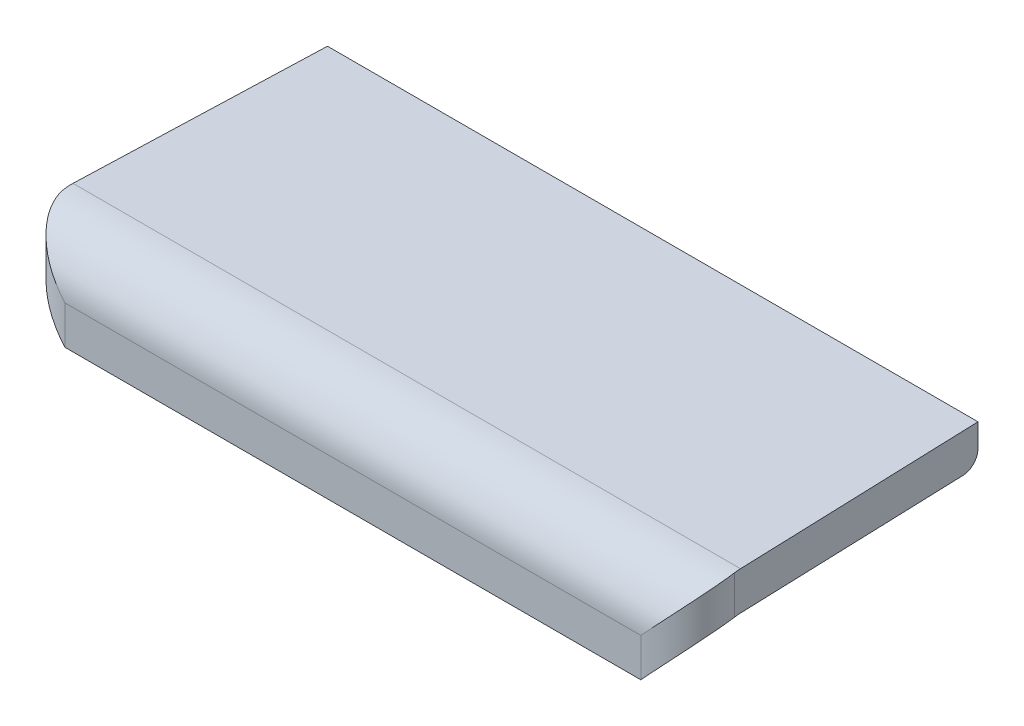
SolidWorks part; units mm, degrees
material "PF"
ref_plane "Спереди" through (0, 0, 0) normal (0, 0, 1) x (1, 0, 0)
ref_plane "Сверху" through (0, 0, 0) normal (0, 1, 0) x (1, 0, 0)
ref_plane "Справа" through (0, 0, 0) normal (1, 0, 0) x (0, 0, -1)
sketch "Эскиз1" plane through (0, 0, 0) normal (1, 0, 0) x (0, 0, -1)
  line L0 (-63.6775, 0) -> (17.5893, 0) construction
  line L1 (0, 14.5278) -> (0, -23.6564) construction
  line L2 (-49.5, 0) -> (0, 0)
  line L4 (-49.5, -2.5) -> (0, -2.5)
  line L5 (0, 0) -> (0, -2.5)
  line L6 (-53, -6) -> (-53, -3.5)
  line L7 (-53, 5.3663) -> (-53, -14.1912) construction
  arc A0 (-53, -6) -> (-49.5, -2.5) centre (-49.5, -6) cw
  arc A1 (-53, -3.5) -> (-49.5, 0) centre (-49.5, -3.5) cw
  point P16 (-53, 0)
  dimension "D3" = 3.5
  dimension "D4" = 3.5
  dimension "D1" = 53
  dimension "D2" = 2.5
extrude "Бобышка-Вытянуть1" add sketch "Эскиз1" along normal mid plane 44
sketch "Эскиз2" plane through (0, 0, 0) normal (0, 1, 0) x (1, 0, 0)
  line L0 (0, 2.7123) -> (0, -68.9812) construction
  line L1 (-30.0519, 0) -> (26.7974, 0) construction
  line L2 (-33.3063, -58) -> (31.5752, -58) construction
  line L3 (-22, -58) -> (-20, 0) construction
  line L4 (21.1552, -33.5) -> (-21.1552, -33.5)
  line L5 (-21.1552, -33.5) -> (-21.7206, -49.8966)
  line L6 (-18.7224, -53) -> (18.7224, -53)
  line L7 (21.1552, -33.5) -> (21.7206, -49.8966)
  line L8 (-22, 0) -> (22, 0)
  line L9 (22, 0) -> (22, -58)
  line L11 (-22, -58) -> (22, -58)
  line L12 (-22, 0) -> (-22, -58)
  line L13 (-22, 0) -> (-22, -49.5) construction
  arc A0 (-18.7224, -53) -> (-21.7206, -49.8966) centre (-18.7224, -50) cw
  arc A1 (18.7224, -53) -> (21.7206, -49.8966) centre (18.7224, -50) ccw
  point P15 (-21.8276, -53)
  point P17 (0, -53)
  point P20 (0, -33.5)
  dimension "D6" = 3
  dimension "D1" = 58
  dimension "D2" = 22
  dimension "D3" = 20
  dimension "D4" = 33.5
  dimension "D5" = 53
extrude "Вырез-Вытянуть1" cut sketch "Эскиз2" against normal blind 7
fillet "Скругление1" radius 1 1 edges at (0, -2.5, 33.5)
sketch "Эскиз3" plane through (0, 0, 0) normal (1, 0, 0) x (0, 0, -1)
  line L0 (2.7845, 0) -> (-59.9685, 0) construction
  line L1 (0, 5.2444) -> (0, -9.0545) construction
  line L2 (-47, -8) -> (-47, -2.5)
  line L3 (-49.5, -2.5) -> (-34.5, -2.5) construction
  line L4 (-47, -2.5) -> (-41, -2.5)
  line L5 (-41, -2.5) -> (-41, -8)
  arc A0 (-47, -8) -> (-41, -8) centre (-44, -8) ccw
  circle A1 centre (-44, -8) radius 2
  dimension "D3" = 3
  dimension "D4" = 4
  dimension "D1" = 44
  dimension "D2" = 8
extrude "Бобышка-Вытянуть2" add sketch "Эскиз3" along normal mid plane 20
